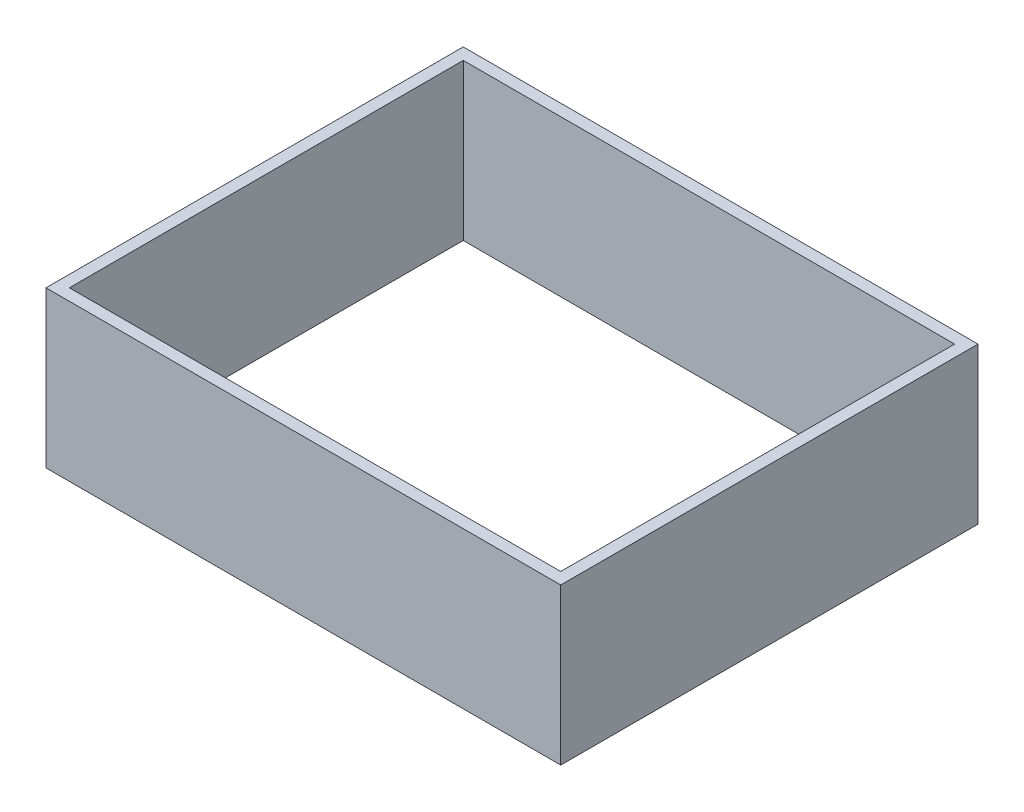
SolidWorks part; units mm, degrees
ref_plane "前视基准面" through (0, 0, 0) normal (0, 0, 1) x (1, 0, 0)
ref_plane "上视基准面" through (0, 0, 0) normal (0, 1, 0) x (1, 0, 0)
ref_plane "右视基准面" through (0, 0, 0) normal (1, 0, 0) x (0, 0, -1)
other "Configuration Table"
sketch "草图1" plane through (0, 0, 0) normal (0, 0, 1) x (1, 0, 0)
  line L8 (-33, -10) -> (33, -10)
  line L9 (33, -10) -> (33, 10)
  line L10 (33, 10) -> (-33, 10)
  line L11 (-33, 10) -> (-33, -10)
extrude "绑带底段" add sketch "草图1" along normal blind 1.5
sketch "草图2" plane through (0, 0, 0) normal (0, 0, 1) x (1, 0, 0)
  line L16 (-33, -10) -> (-31.5, -10)
  line L17 (-31.5, -10) -> (-31.5, 10)
  line L18 (-31.5, 10) -> (-33, 10)
  line L19 (-33, 10) -> (-33, -10)
  line L20 (31.5, -10) -> (33, -10)
  line L21 (33, -10) -> (33, 10)
  line L22 (33, 10) -> (31.5, 10)
  line L23 (31.5, 10) -> (31.5, -10)
extrude "绑带侧段" add sketch "草图2" along normal blind 50.5 from offset 1.5
sketch "草图3" plane through (0, 0, 0) normal (0, 0, 1) x (1, 0, 0)
  line L8 (-33, -10) -> (33, -10)
  line L9 (33, -10) -> (33, 10)
  line L10 (33, 10) -> (-33, 10)
  line L11 (-33, 10) -> (-33, -10)
extrude "绑带上段" add sketch "草图3" along normal blind 1.5 from offset 52
